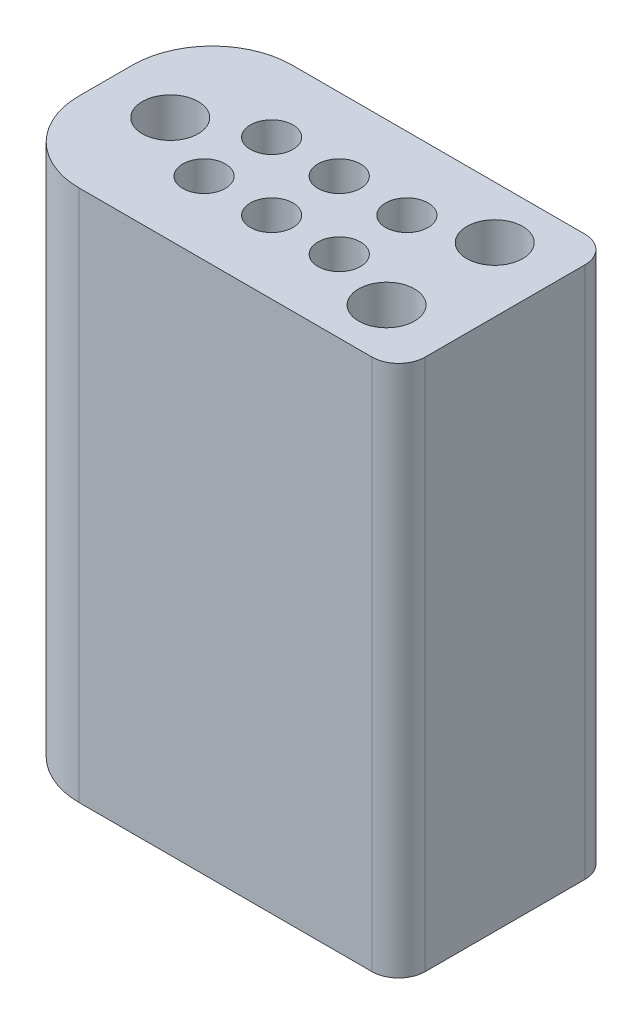
SolidWorks part; units mm, degrees
ref_plane "Front Plane" through (0, 0, 0) normal (0, 0, 1) x (1, 0, 0)
ref_plane "Top Plane" through (0, 0, 0) normal (0, 1, 0) x (1, 0, 0)
ref_plane "Right Plane" through (0, 0, 0) normal (1, 0, 0) x (0, 0, -1)
sketch "Sketch1" plane through (0, 0, 0) normal (0, 1, 0) x (1, 0, 0)
  line L0 (-1.27, 0.635) -> (1.27, 0.635) construction
  line L1 (1.27, 0.635) -> (1.27, -0.635) construction
  line L2 (1.27, -0.635) -> (-1.27, -0.635) construction
  line L3 (-1.27, -0.635) -> (-1.27, 0.635) construction
  line L4 (2.54, 1.016) -> (2.54, -1.016) construction
  line L5 (2.54, 1.016) -> (-2.54, 1.016) construction
  line L6 (-2.54, 1.016) -> (-2.54, -1.016) construction
  line L7 (-2.54, -1.016) -> (2.54, -1.016) construction
  line L9 (-2.25, 2) -> (3.25, 2)
  line L10 (-3.75, 0.5) -> (-3.75, -0.5)
  line L11 (-2.25, -2) -> (3.25, -2)
  line L12 (3.75, 1.5) -> (3.75, -1.5)
  circle A0 centre (0, 0.635) radius 0.4
  circle A1 centre (0, -0.635) radius 0.4
  circle A2 centre (-1.27, -0.635) radius 0.4
  circle A3 centre (-1.27, 0.635) radius 0.4
  circle A4 centre (1.27, 0.635) radius 0.4
  circle A5 centre (1.27, -0.635) radius 0.4
  circle A6 centre (2.54, 1.016) radius 0.525
  circle A7 centre (2.54, -1.016) radius 0.525
  circle A8 centre (-2.54, 0) radius 0.525
  arc A9 (-3.75, -0.5) -> (-2.25, -2) centre (-2.25, -0.5) ccw
  arc A10 (-2.25, 2) -> (-3.75, 0.5) centre (-2.25, 0.5) ccw
  arc A11 (3.25, -2) -> (3.75, -1.5) centre (3.25, -1.5) ccw
  arc A12 (3.25, 2) -> (3.75, 1.5) centre (3.25, 1.5) cw
  point P27 (-3.75, -2)
  point P30 (-3.75, 2)
  point P35 (3.75, 2)
  dimension "D9" = 0.8
  dimension "D10" = 0.8
  dimension "D11" = 0.8
  dimension "D12" = 0.8
  dimension "D13" = 0.8
  dimension "D14" = 0.8
  dimension "D15" = 1.05
  dimension "D16" = 1.05
  dimension "D17" = 1.05
  dimension "D22" = 1.5
  dimension "D23" = 0.5
  dimension "D1" = 0.635
  dimension "D2" = 0.635
  dimension "D3" = 1.27
  dimension "D4" = 1.27
  dimension "D5" = 2.54
  dimension "D6" = 1.016
  dimension "D7" = 1.016
  dimension "D8" = 2.54
  dimension "D18" = 4
  dimension "D19" = 7.5
  dimension "D20" = 2
  dimension "D21" = 3.75
extrude "Boss-Extrude1" add sketch "Sketch1" along normal blind 10
